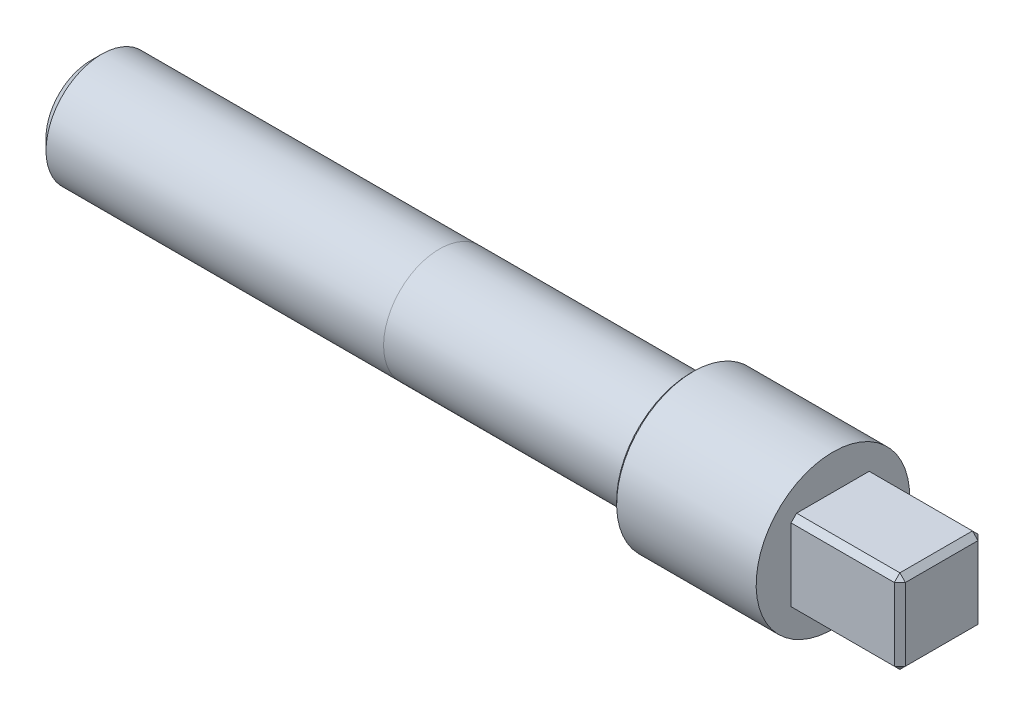
SolidWorks part; units mm, degrees
ref_plane "前视基准面" through (0, 0, 0) normal (0, 0, 1) x (1, 0, 0)
ref_plane "上视基准面" through (0, 0, 0) normal (0, 1, 0) x (1, 0, 0)
ref_plane "右视基准面" through (0, 0, 0) normal (1, 0, 0) x (0, 0, -1)
sketch "草图1" plane through (0, 0, 0) normal (1, 0, 0) x (0, -1, 0)
  circle A0 centre (0, 0) radius 20
  dimension "D1" = 40
extrude "凸台-拉伸1" add sketch "草图1" along normal blind 215
sketch "草图2" plane through (215, 0, 0) normal (1, 0, 0) x (0, -1, 0)
  circle A0 centre (0, 0) radius 27.5
  dimension "D1" = 55
extrude "凸台-拉伸2" add sketch "草图2" along normal blind 51
sketch "草图3" plane through (266, 0, 0) normal (1, 0, 0) x (0, -1, 0)
  line L0 (-1000, 0) -> (49000, 0) construction
  line L1 (-15, 15) -> (15, 15)
  line L2 (-15, 15) -> (-15, -15)
  line L3 (-15, -15) -> (15, -15)
  line L4 (15, 15) -> (15, -15)
  line L5 (0, -1000) -> (0, 49000) construction
  dimension "D1" = 30
  dimension "D2" = 30
extrude "凸台-拉伸3" add sketch "草图3" along normal blind 39
chamfer "倒角2" distance 1 angle 45 1 edges at (215, 27.5, 0)
chamfer "倒角3" distance 2 angle 45 8 edges at (285.5, -15, 15) (305, -15, 0) (305, 0, -15) (285.5, 15, -15) (285.5, 15, 15) (305, 0, 15) (305, 15, 0) (285.5, -15, -15)
sketch "草图4" plane through (0, 0, 0) normal (-1, 0, 0) x (0, -1, 0)
  circle A0 centre (0, 0) radius 20
  circle A1 centre (0, 0) radius 19.975
  dimension "D1" = 40
  dimension "D2" = 39.95
extrude "切除-拉伸1" cut sketch "草图4" against normal blind 125
chamfer "倒角4" distance 4 angle 45 1 edges at (0, -19.975, 0)
